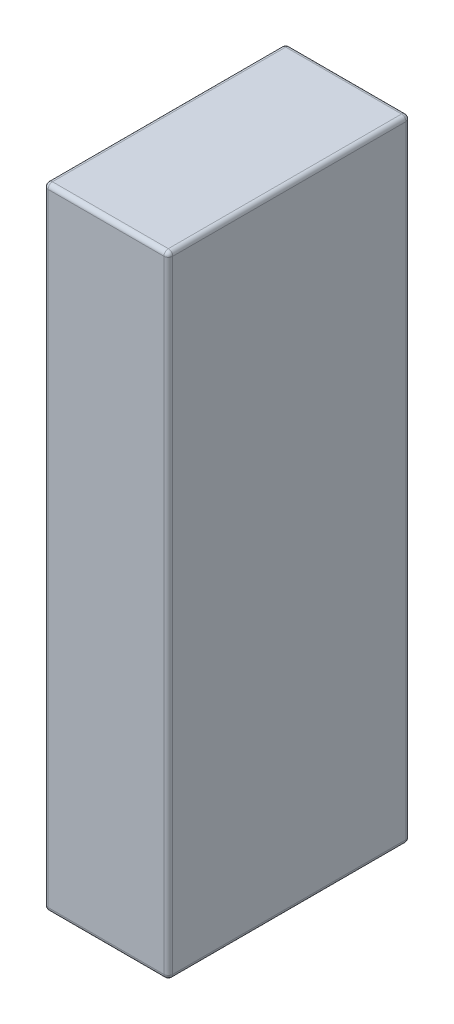
SolidWorks part; units mm, degrees
ref_plane "Alzado" through (0, 0, 0) normal (0, 0, 1) x (1, 0, 0)
ref_plane "Planta" through (0, 0, 0) normal (0, 1, 0) x (1, 0, 0)
ref_plane "Vista lateral" through (0, 0, 0) normal (1, 0, 0) x (0, 0, -1)
sketch "Croquis1" plane through (0, 0, 0) normal (0, 0, 1) x (1, 0, 0)
  line L1 (-103.507, 168.3529) -> (-18.507, 168.3529)
  line L2 (-103.507, 168.3529) -> (-103.507, -261.6471)
  line L3 (-103.507, -261.6471) -> (-18.507, -261.6471)
  line L4 (-18.507, 168.3529) -> (-18.507, -261.6471)
  dimension "D1" = 85
  dimension "D2" = 430
extrude "Saliente-Extruir1" add sketch "Croquis1" along normal blind 165
fillet "Redondeo1" radius 3 12 edges at (-103.507, -261.6471, 82.5) (-18.507, -261.6471, 82.5) (-18.507, 168.3529, 82.5) (-103.507, 168.3529, 82.5) (-61.007, 168.3529, 165) (-18.507, -46.6471, 165) (-61.007, -261.6471, 165) (-103.507, -46.6471, 165) (-61.007, 168.3529, 0) (-18.507, -46.6471, 0) (-61.007, -261.6471, 0) (-103.507, -46.6471, 0)
